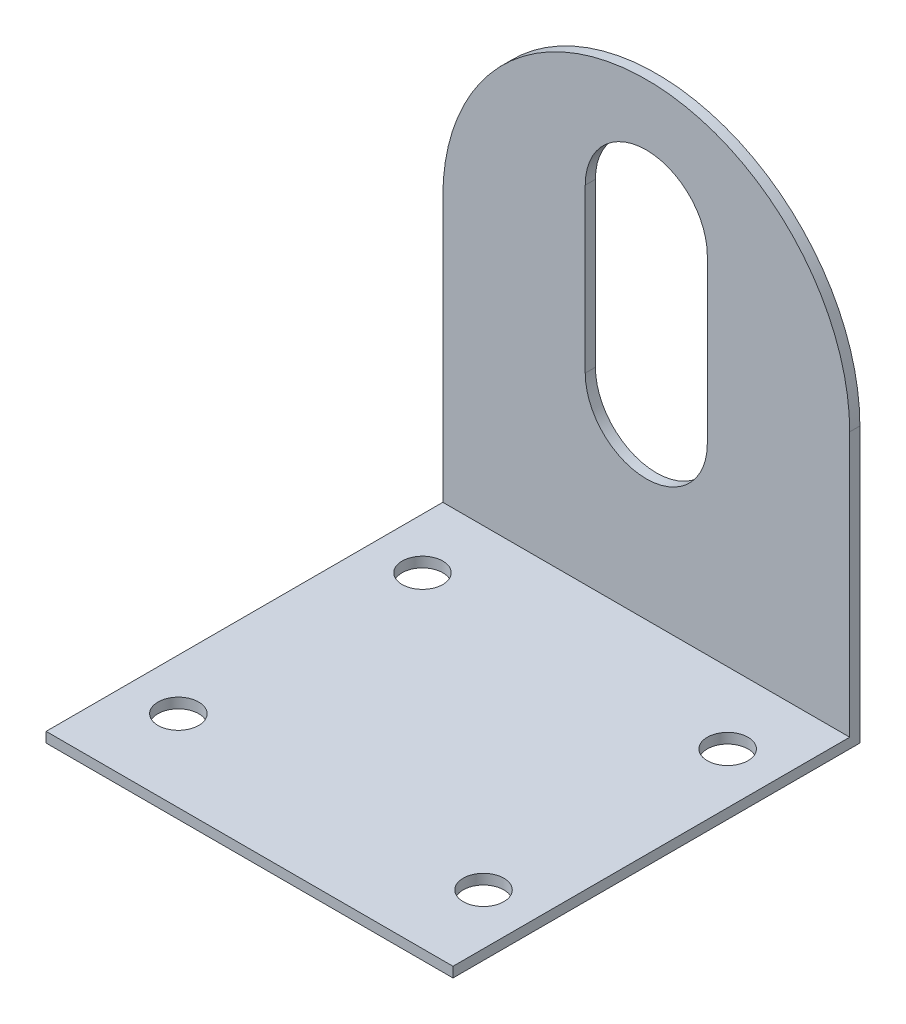
SolidWorks part; units mm, degrees
ref_plane "Front Plane" through (0, 0, 0) normal (0, 0, 1) x (1, 0, 0)
ref_plane "Top Plane" through (0, 0, 0) normal (0, 1, 0) x (1, 0, 0)
ref_plane "Right Plane" through (0, 0, 0) normal (1, 0, 0) x (0, 0, -1)
sketch "Sketch1" plane through (0, 0, 0) normal (0, 1, 0) x (1, 0, 0)
  line L1 (20, -20) -> (-20, -20)
  line L2 (20, -20) -> (20, 20)
  line L3 (20, 20) -> (-20, 20)
  line L4 (-20, -20) -> (-20, 20)
  line L5 (20, -20) -> (-20, 20) construction
  line L6 (20, 20) -> (-20, -20) construction
  circle A0 centre (-15, -12) radius 2
  circle A1 centre (15, -12) radius 2
  circle A2 centre (15, 12) radius 2
  circle A3 centre (-15, 12) radius 2
  point P0 (0, 0)
  point P14 (0, 0)
  point P16 (-17.0188, -20)
  dimension "D3" = 4
  dimension "D1" = 40
  dimension "D2" = 40
  dimension "D4" = 30
  dimension "D5" = 5
  dimension "D6" = 8
  dimension "D7" = 8
extrude "Boss-Extrude1" add sketch "Sketch1" along normal blind 1
sketch "Sketch2" plane through (0, 1, 0) normal (0, 1, 0) x (1, 0, 0)
  line L0 (20, -20) -> (20, 20) construction
  line L1 (-20, 20) -> (20, 20)
  line L2 (-20, 20) -> (-20, 19)
  line L3 (-20, 19) -> (20, 19)
  line L4 (20, 20) -> (20, 19)
  dimension "D1" = 1
extrude "Boss-Extrude2" add sketch "Sketch2" along normal blind 46
sketch "Sketch3" plane through (0, 0, -19) normal (0, 0, 1) x (1, 0, 0)
  line L0 (0, 35) -> (0, 19) construction
  line L1 (6, 35) -> (6, 19)
  line L2 (-6, 35) -> (-6, 19)
  line L4 (-20, 1) -> (20, 1)
  line L5 (20, 1) -> (20, 47)
  line L6 (20, 47) -> (-20, 47)
  line L7 (-20, 47) -> (-20, 1)
  line L9 (20, 27) -> (20, 47)
  line L10 (20, 47) -> (-20, 47)
  line L11 (-20, 47) -> (-20, 27)
  arc A0 (20, 27) -> (-20, 27) centre (0, 27) ccw
  arc A1 (6, 35) -> (-6, 35) centre (0, 35) ccw
  arc A2 (-6, 19) -> (6, 19) centre (0, 19) ccw
  point P10 (0, 27)
  dimension "D2" = 12
  dimension "D3" = 12
  dimension "D4" = 16
  dimension "D1" = 0
extrude "Cut-Extrude1" cut sketch "Sketch3" against normal blind 46
